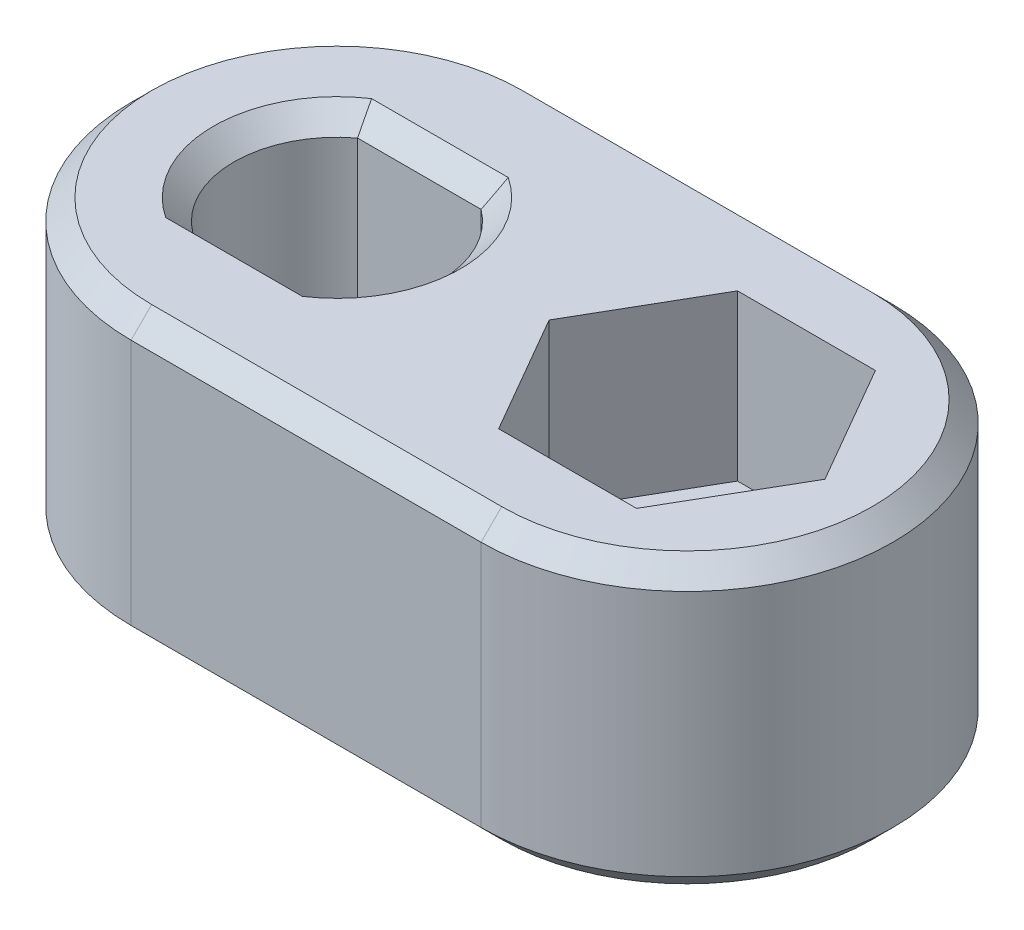
SolidWorks part; units mm, degrees
ref_plane "前视基准面" through (0, 0, 0) normal (0, 0, 1) x (1, 0, 0)
ref_plane "上视基准面" through (0, 0, 0) normal (0, 1, 0) x (1, 0, 0)
ref_plane "右视基准面" through (0, 0, 0) normal (1, 0, 0) x (0, 0, -1)
sketch "草图1" plane through (0, 0, 0) normal (0, 1, 0) x (1, 0, 0)
  line L0 (0, 0) -> (8.5, 0) construction
  line L1 (0, 5) -> (8.5, 5)
  line L2 (0, -5) -> (8.5, -5)
  arc A0 (0, 5) -> (0, -5) centre (0, 0) ccw
  arc A1 (8.5, -5) -> (8.5, 5) centre (8.5, 0) ccw
  point P3 (4.25, 0)
  dimension "D1" = 10
  dimension "D2" = 8.5
extrude "凸台-拉伸1" add sketch "草图1" along normal blind 7
sketch "草图2" plane through (0, 7, 0) normal (0, 1, 0) x (1, 0, 0)
  line L1 (1.5, 2) -> (-1.5, 2)
  line L2 (-1.5, -2) -> (1.5, -2)
  line L3 (-3.2117, 0) -> (4.4357, 0) construction
  circle A0 centre (0, 0) radius 2.5
  dimension "D1" = 4
  dimension "D2" = 5
extrude "切除-拉伸1" cut sketch "草图2" against normal blind 4 contours A0 L3 L1 | L3 A0 L2
hole_wizard "M3 六角凹锥坑螺钉的锥形沉头孔1" positions "草图5" profile "草图4" countersink size "M3" standard "ISO"
sketch "草图5" plane through (0, 0, 0) normal (0, -1, 0) x (-1, 0, 0)
  point P0 (0, 0)
sketch "草图4" plane through (0, 0, 0) normal (1, 0, 0) x (0, 0, -1)
  line L0 (0, 0) -> (0, 8.5215)
  line L1 (0, 8.5215) -> (1.7, 7.5)
  line L2 (1.7, 7.5) -> (1.7, 1.66)
  line L3 (1.7, 1.66) -> (3.36, 0)
  line L5 (3.36, 0) -> (0, 0)
  line L6 (-1.7, 1.66) -> (-3.36, 0) construction
  line L10 (0, 8.5215) -> (-1.7, 7.5) construction
  line L11 (0, -6.35) -> (0, 107.95) construction
  dimension "孔直径" = 3.4
  dimension "孔深度" = 7.5
  dimension "近端锥形沉头孔直径" = 6.72
  dimension "近端锥形沉头孔角度" = 90
  dimension "导头角度" = 118
hole_wizard "孔1" positions "草图6" profile "草图7" legacy end condition through all
sketch "草图6" plane through (0, 0, 0) normal (0, -1, 0) x (-1, 0, 0)
  point P0 (-8.5, 0)
sketch "草图7" plane through (8.5, 0, 0) normal (1, 0, 0) x (0, 0, -1)
  line L0 (0, 0) -> (0, 7)
  line L1 (0, 7) -> (2.075, 7)
  line L2 (2.075, 7) -> (2.075, 0)
  line L3 (2.075, 0) -> (0, 0)
  line L4 (0, 110) -> (0, -10) construction
  dimension "直径" = 4.15
  dimension "深度" = 7
sketch "草图8" plane through (0, 7, 0) normal (0, 1, 0) x (1, 0, 0)
sketch "草图9" plane through (0, 7, 0) normal (0, 1, 0) x (1, 0, 0)
  line L0 (8.5, 5) -> (0, 5) construction
  line L1 (10.1743, 2.9) -> (6.8257, 2.9)
  line L2 (6.8257, 2.9) -> (5.1514, 0)
  line L3 (5.1514, 0) -> (6.8257, -2.9)
  line L4 (6.8257, -2.9) -> (10.1743, -2.9)
  line L5 (10.1743, -2.9) -> (11.8486, 0)
  line L6 (11.8486, 0) -> (10.1743, 2.9)
  circle A0 centre (8.5, 0) radius 2.9 construction
  dimension "D1" = 5.8
extrude "切除-拉伸2" cut sketch "草图9" against normal blind 4
chamfer "倒角1" distance 0.5 angle 45 12 edges at (0, 7, 2) (-2.5, 7, 0) (2.5, 7, 0) (0, 7, -2) (4.25, 7, 5) (13.5, 7, 0) (-5, 7, 0) (4.25, 7, -5) (4.25, 0, 5) (13.5, 0, 0) (-5, 0, 0) (4.25, 0, -5)
